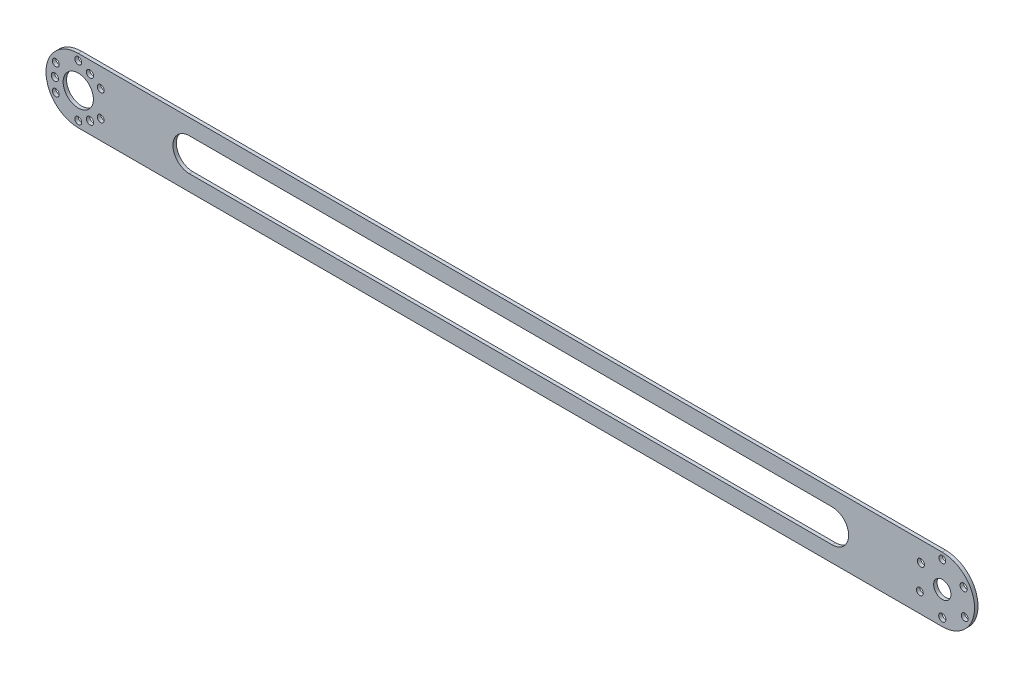
SolidWorks part; units mm, degrees
ref_plane "前视基准面" through (0, 0, 0) normal (0, 0, 1) x (1, 0, 0)
ref_plane "上视基准面" through (0, 0, 0) normal (0, 1, 0) x (1, 0, 0)
ref_plane "右视基准面" through (0, 0, 0) normal (1, 0, 0) x (0, 0, -1)
sketch "草图1" plane through (0, 0, 0) normal (0, 0, 1) x (1, 0, 0)
  line L0 (341.7971, -84.9071) -> (328.8068, -92.4071) construction
  line L1 (341.7971, -84.9071) -> (324.2622, -74.7833) construction
  line L2 (-157.62, -84.9071) -> (-157.62, -88.257) construction
  line L3 (-157.62, -84.9071) -> (342.38, -84.9071) construction
  line L4 (341.7971, -66.2614) -> (-157.62, -66.2614)
  line L5 (-157.62, -103.5529) -> (341.7971, -103.5529)
  line L6 (-93.422, -84.9071) -> (278.1819, -84.9071) construction
  line L7 (-93.422, -75.424) -> (278.1819, -75.424)
  line L8 (-93.422, -94.3902) -> (278.1819, -94.3902)
  circle A0 centre (341.7971, -84.9071) radius 5
  circle A1 centre (341.7971, -84.9071) radius 15 construction
  circle A2 centre (341.7971, -84.9071) radius 14.25 construction
  circle A3 centre (341.7971, -69.9071) radius 2
  circle A4 centre (354.7875, -92.2614) radius 2
  circle A5 centre (328.8068, -92.4071) radius 2
  circle A6 centre (329.4345, -77.7696) radius 2.08
  circle A7 centre (354.1597, -77.6239) radius 2.08
  circle A8 centre (341.7971, -99.0365) radius 2.08
  circle A9 centre (341.7971, -84.9071) radius 18.6457 construction
  circle A10 centre (-157.62, -84.9071) radius 15 construction
  circle A11 centre (-157.62, -84.9071) radius 13.53 construction
  circle A12 centre (-157.62, -99.9071) radius 2
  circle A13 centre (-170.6104, -92.4071) radius 2
  circle A14 centre (-170.6104, -77.4071) radius 2
  circle A15 centre (-157.62, -69.9071) radius 2
  circle A16 centre (-144.6296, -77.4071) radius 2
  circle A17 centre (-144.6296, -92.4071) radius 2
  circle A18 centre (-171.15, -84.9071) radius 2.08
  circle A19 centre (-150.855, -73.1898) radius 2.08
  circle A20 centre (-150.855, -96.6245) radius 2.08
  circle A21 centre (-157.62, -84.9071) radius 8.75
  circle A22 centre (-157.62, -84.9071) radius 18.6457 construction
  arc A23 (341.7971, -66.2614) -> (341.7971, -103.5529) centre (341.7971, -84.9071) cw
  arc A24 (-157.62, -103.5529) -> (-157.62, -66.2614) centre (-157.62, -84.9071) cw
  arc A25 (-93.422, -75.424) -> (-93.422, -94.3902) centre (-93.422, -84.9071) ccw
  arc A26 (278.1819, -94.3902) -> (278.1819, -75.424) centre (278.1819, -84.9071) ccw
  point P51 (92.38, -84.9071)
  dimension "D1" = 60
extrude "凸台-拉伸1" add sketch "草图1" along normal blind 2 contours A9
